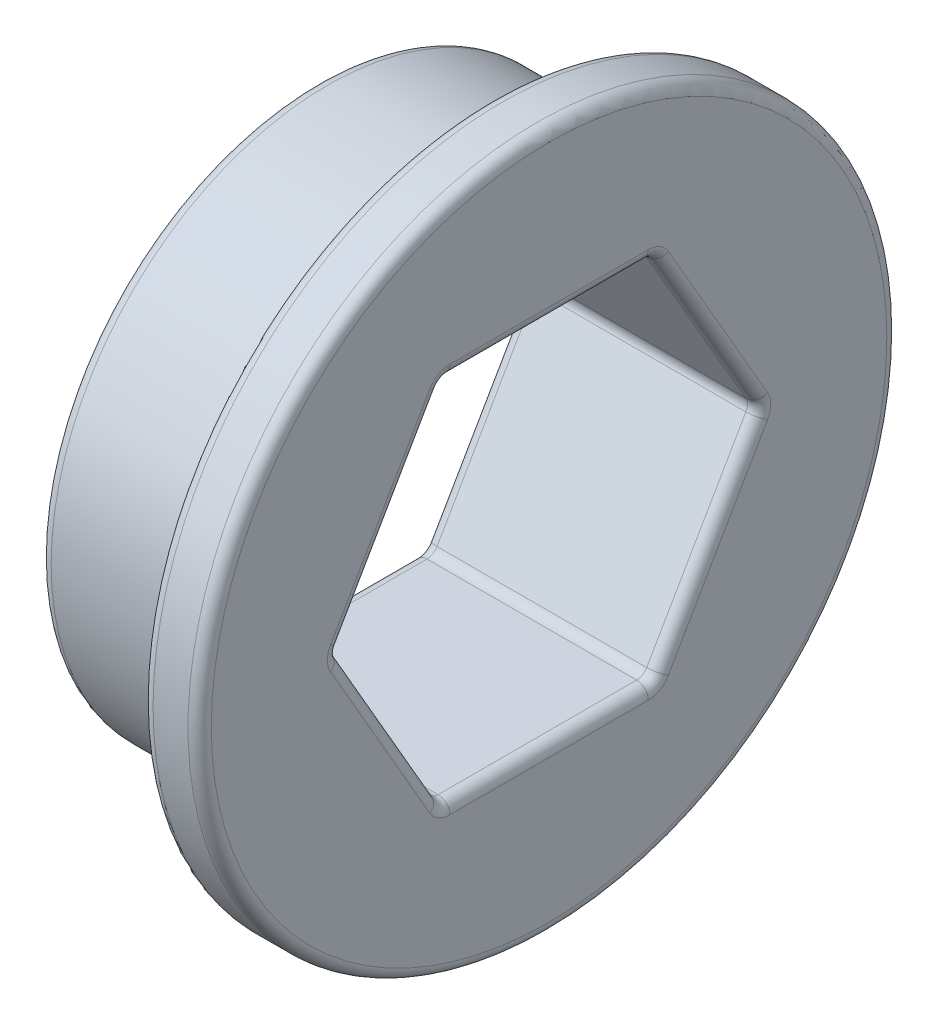
SolidWorks part; units mm, degrees
ref_plane "Front Plane" through (0, 0, 0) normal (0, 0, 1) x (1, 0, 0)
ref_plane "Top Plane" through (0, 0, 0) normal (0, 1, 0) x (1, 0, 0)
ref_plane "Right Plane" through (0, 0, 0) normal (1, 0, 0) x (0, 0, -1)
sketch "Sketch1" plane through (0, 0, 0) normal (0, 0, 1) x (1, 0, 0)
  line L0 (0, 0) -> (-8.0549, 0) construction
  line L1 (-4, 0) -> (-4, 4.75)
  line L2 (-4, 4.75) -> (-1, 4.75)
  line L3 (-1, 4.75) -> (-1, 6)
  line L4 (-1, 6) -> (0, 6)
  line L5 (0, 6) -> (0, 0)
  line L6 (0, 0) -> (-4, 0)
  dimension "D1" = 12
  dimension "D2" = 1
  dimension "D3" = 3
  dimension "D4" = 9.5
revolve "Revolve1" add sketch "Sketch1" angle 360 about L0
sketch "Sketch2" plane through (0, 0, 0) normal (1, 0, 0) x (0, 0, -1)
  line L2 (3.6373, 0) -> (1.8187, 3.15)
  line L3 (1.8187, 3.15) -> (-1.8187, 3.15)
  line L4 (-1.8187, 3.15) -> (-3.6373, 0)
  line L5 (-3.6373, 0) -> (-1.8187, -3.15)
  line L6 (-1.8187, -3.15) -> (1.8187, -3.15)
  line L7 (1.8187, -3.15) -> (3.6373, 0)
  circle A1 centre (0, 0) radius 3.15 construction
  point P1 (0, 0)
  dimension "D1" = 6.3
extrude "Cut-Extrude1" cut sketch "Sketch2" against normal up to next
fillet "Fillet1" radius 0.2 22 edges at (0, 0, -6) (-1, 0, -6) (-1, 0, -4.75) (-4, 0, -4.75) (-4, 3.15, 0) (0, 3.15, 0) (-4, -1.575, 2.728) (-4, -1.575, -2.728) (0, -1.575, -2.728) (0, -1.575, 2.728) (-4, 1.575, -2.728) (-2, 3.15, -1.8187) (0, 1.575, -2.728) (-2, 0, -3.6373) (-4, 1.575, 2.728) (-2, 0, 3.6373) (0, 1.575, 2.728) (-2, 3.15, 1.8187) (-4, -3.15, 0) (-2, -3.15, -1.8187) (0, -3.15, 0) (-2, -3.15, 1.8187)
